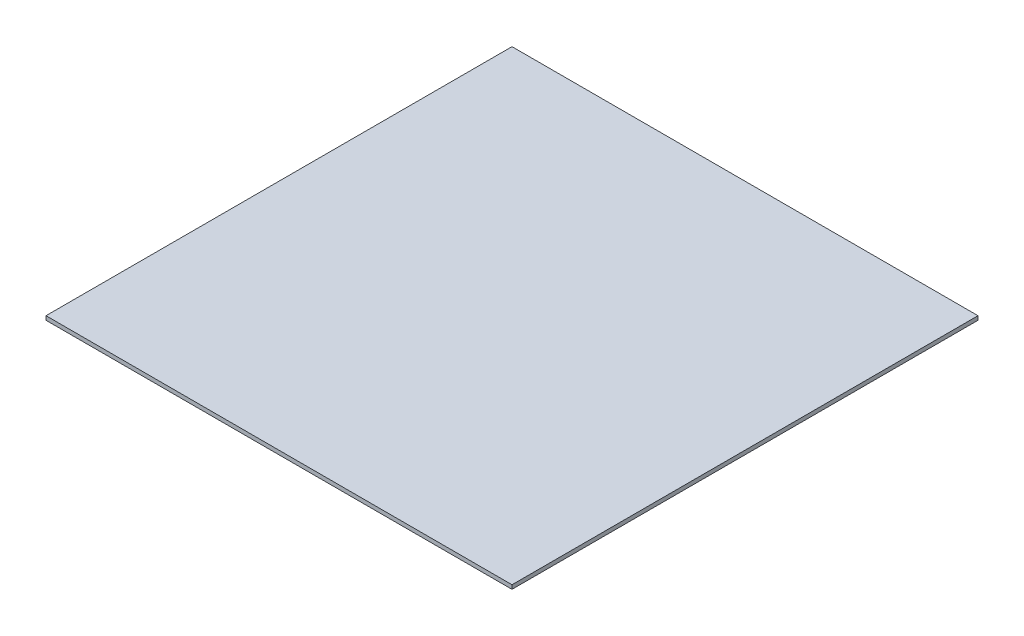
SolidWorks part; units mm, degrees
material "7075-T6 (SN)"
ref_plane "Front Plane" through (0, 0, 0) normal (0, 0, 1) x (1, 0, 0)
ref_plane "Top Plane" through (0, 0, 0) normal (0, 1, 0) x (1, 0, 0)
ref_plane "Right Plane" through (0, 0, 0) normal (1, 0, 0) x (0, 0, -1)
sketch "Sketch1" plane through (0, 0, 0) normal (0, 1, 0) x (1, 0, 0)
  line L1 (-350, 350) -> (350, 350)
  line L2 (-350, 350) -> (-350, -350)
  line L3 (-350, -350) -> (350, -350)
  line L4 (350, 350) -> (350, -350)
  line L5 (-350, 350) -> (350, -350) construction
  line L6 (-350, -350) -> (350, 350) construction
  point P0 (0, 0)
  dimension "D1" = 700
  dimension "D2" = 700
extrude "Boss-Extrude1" add sketch "Sketch1" along normal blind 6
